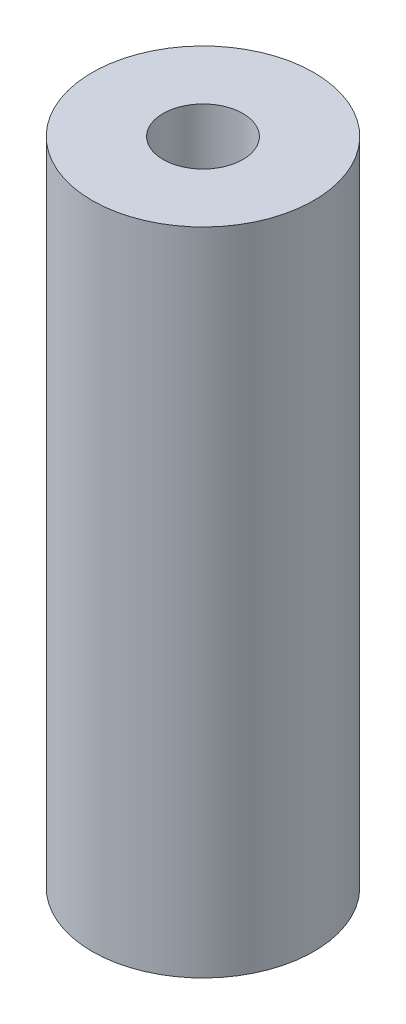
SolidWorks part; units mm, degrees
ref_plane "Front Plane" through (0, 0, 0) normal (0, 0, 1) x (1, 0, 0)
ref_plane "Top Plane" through (0, 0, 0) normal (0, 1, 0) x (1, 0, 0)
ref_plane "Right Plane" through (0, 0, 0) normal (1, 0, 0) x (0, 0, -1)
sketch "Sketch1" plane through (0, 0, 0) normal (0, 1, 0) x (1, 0, 0)
  circle A0 centre (0, 0) radius 3.75
  dimension "D1" = 7.5
extrude "Boss-Extrude1" add sketch "Sketch1" along normal blind 22 contours A0
sketch "Sketch2" plane through (0, 0, 0) normal (0, -1, 0) x (1, 0, 0)
  circle A0 centre (0, 0) radius 1.35
  dimension "D1" = 2.7
extrude "Cut-Extrude1" cut sketch "Sketch2" against normal through all
